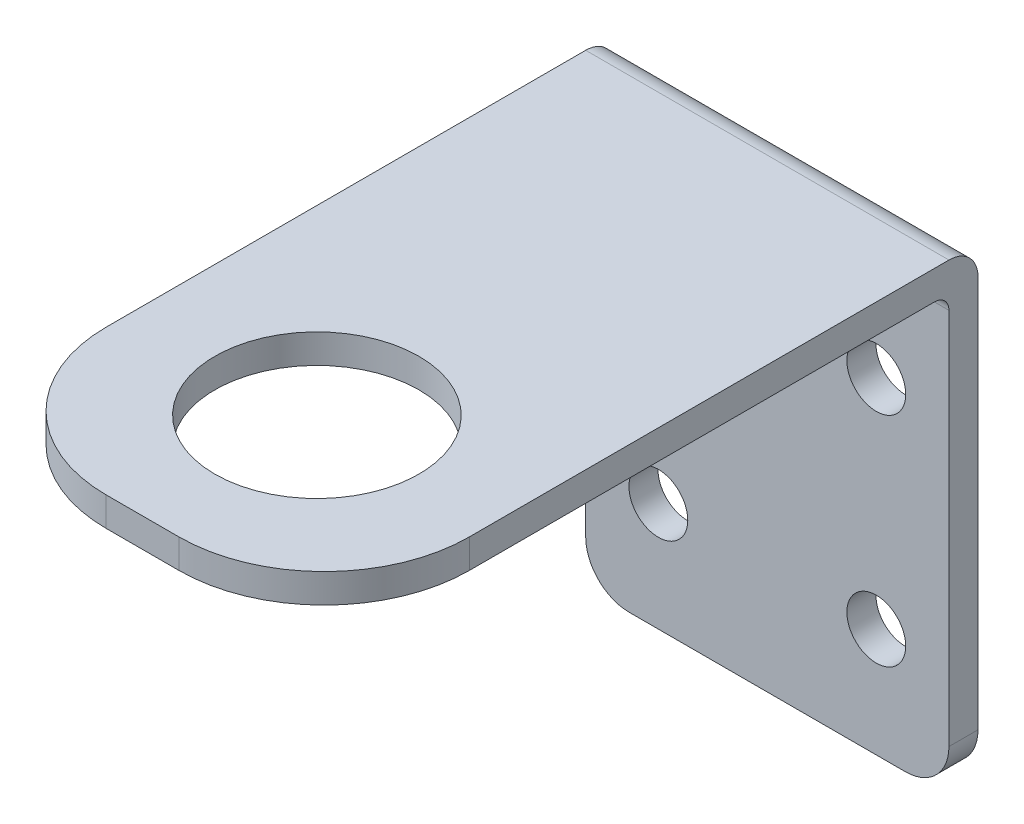
SolidWorks part; units mm, degrees
material "AISI 304"
ref_plane "Front Plane" through (0, 0, 0) normal (0, 0, 1) x (1, 0, 0)
ref_plane "Top Plane" through (0, 0, 0) normal (0, 1, 0) x (1, 0, 0)
ref_plane "Right Plane" through (0, 0, 0) normal (1, 0, 0) x (0, 0, -1)
sketch "Sketch1" plane through (0, 0, 0) normal (0, 0, 1) x (1, 0, 0)
  line L1 (-12.5, 15) -> (12.5, 15)
  line L2 (-12.5, 15) -> (-12.5, -15)
  line L3 (-12.5, -15) -> (12.5, -15)
  line L4 (12.5, 15) -> (12.5, -15)
  line L5 (-12.5, 15) -> (12.5, -15) construction
  line L6 (-12.5, -15) -> (12.5, 15) construction
  point P0 (0, 0)
  dimension "D1" = 25
  dimension "D2" = 30
extrude "Boss-Extrude1" add sketch "Sketch1" along normal blind 2
sketch "Sketch2" plane through (0, 0, 2) normal (0, 0, 1) x (1, 0, 0)
  line L0 (0, 10.8803) -> (0, -11.0779) construction
  line L1 (-15.0293, 0) -> (15.0589, 0) construction
  line L2 (-7.5, 10.8803) -> (-7.5, -11.0779) construction
  line L3 (7.5, 10.8803) -> (7.5, -11.0779) construction
  line L4 (-15.0293, -7.5) -> (15.0589, -7.5) construction
  line L5 (-15.0293, 7.5) -> (15.0589, 7.5) construction
  circle A0 centre (-7.5, 7.5) radius 2.025
  circle A1 centre (7.5, 7.5) radius 2.025
  circle A2 centre (7.5, -7.5) radius 2.025
  circle A3 centre (-7.5, -7.5) radius 2.025
  point P15 (7.5, -6.0985)
  point P16 (7.5, -7.5)
  dimension "D5" = 4.05
  dimension "D8" = 15
  dimension "D1" = 7.5
  dimension "D2" = 7.5
  dimension "D3" = 7.5
  dimension "D4" = 7.5
  dimension "D6" = 2
  dimension "D7" = 2
extrude "Cut-Extrude1" cut sketch "Sketch2" against normal through all
sketch "Sketch3" plane through (0, 0, 0) normal (0, 0, -1) x (-1, 0, 0)
  line L0 (-12.5, 15) -> (-12.5, 17)
  line L1 (-12.5, 17) -> (12.5, 17)
  line L2 (12.5, 17) -> (12.5, 15)
  line L3 (12.5, 15) -> (-12.5, 15)
  dimension "D1" = 2
extrude "Boss-Extrude2" add sketch "Sketch3" against normal blind 45
fillet "Fillet1" radius 2 1 edges at (0, 17, 0)
fillet "Fillet2" radius 1 1 edges at (0, 15, 2)
sketch "Sketch4" plane through (0, 17, 0) normal (0, 1, 0) x (1, 0, 0)
  line L0 (0, 5.1611) -> (0, -54.1369) construction
  line L2 (-12.5, -45) -> (12.5, -45) construction
  circle A0 centre (0, -33) radius 7.025
  dimension "D1" = 14.05
  dimension "D2" = 12
extrude "Cut-Extrude2" cut sketch "Sketch4" against normal through all
fillet "Fillet6" radius 10 2 edges at (12.5, 16, 45) (-12.5, 16, 45)
fillet "Fillet7" radius 3 2 edges at (-12.5, -15, 1) (12.5, -15, 1)
